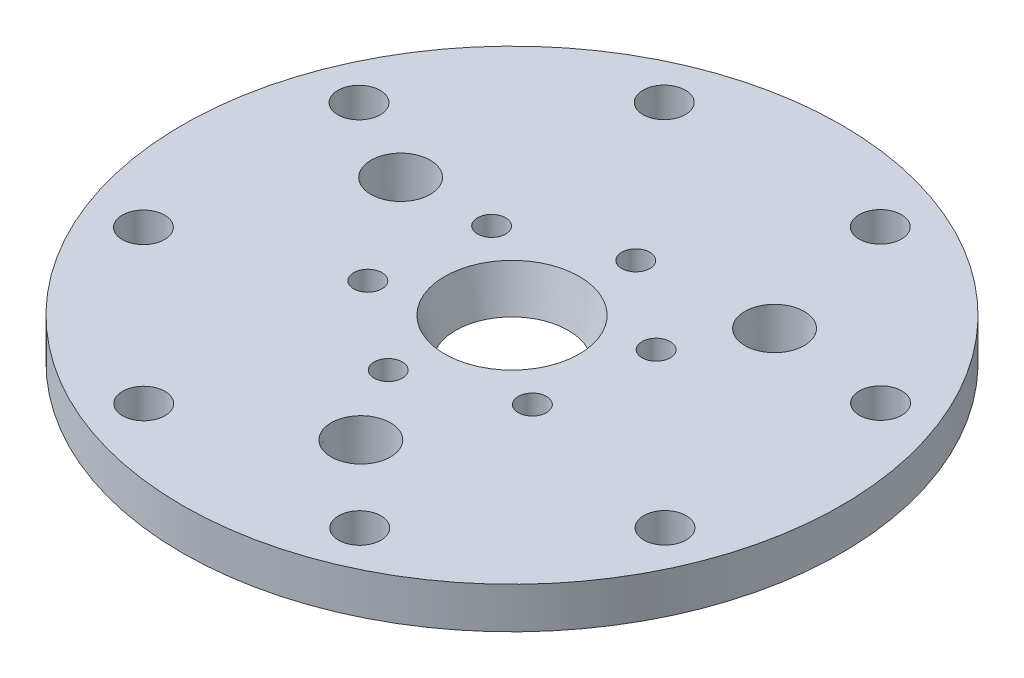
SolidWorks part; units mm, degrees
material "AISI 1020"
ref_plane "Front Plane" through (0, 0, 0) normal (0, 0, 1) x (1, 0, 0)
ref_plane "Top Plane" through (0, 0, 0) normal (0, 1, 0) x (1, 0, 0)
ref_plane "Right Plane" through (0, 0, 0) normal (1, 0, 0) x (0, 0, -1)
sketch "Sketch1" plane through (0, 0, 0) normal (0, 1, 0) x (1, 0, 0)
  circle A0 centre (0, 0) radius 76.2
  dimension "D1" = 152.4
extrude "Boss-Extrude1" add sketch "Sketch1" along normal blind 9.525 contours A0
sketch "Sketch5" plane through (0, 0, 0) normal (0, 0, 1) x (1, 0, 0)
  line L0 (0, 0) -> (0, 29.9809) construction
  line L1 (0, 0) -> (0, 9.525)
  line L2 (13, 0) -> (15.5522, 9.525)
  line L4 (76.2, 9.525) -> (-76.2, 9.525) construction
  line L6 (-76.2, 0) -> (76.2, 0) construction
  line L7 (0, 0) -> (13, 0)
  line L8 (15.5522, 9.525) -> (0, 9.525)
  line L9 (13, 0) -> (13, 9.525) construction
  dimension "D1" = 13
  dimension "D3" = 15
revolve "Cut-Revolve1" cut sketch "Sketch5" angle 360 about L0
sketch "Sketch6" plane through (0, 0, 0) normal (0, 1, 0) x (1, 0, 0)
  line L0 (0, 0) -> (46.194, 19.1342) construction
  line L1 (0, 0) -> (76.2, 0) construction
  circle A0 centre (46.194, 19.1342) radius 2.75
  circle A1 centre (0, 0) radius 76.2 construction
  dimension "D1" = 5.5
  dimension "D2" = 50
  dimension "D3" = 22.5
extrude "Cut-Extrude3" [suppressed] cut sketch "Sketch6" along normal through all
pattern_circular "CirPattern1" [suppressed] count 8 over 360
sketch "Sketch7" plane through (0, 9.525, 0) normal (0, 1, 0) x (1, 0, 0)
  line L0 (0, 0) -> (33.0117, 27.7001) construction
  line L1 (0, 0) -> (54.5383, 0) construction
  circle A0 centre (33.0117, 27.7001) radius 6.35
  circle A1 centre (0, 0) radius 55 construction
  circle A2 centre (33.0117, 27.7001) radius 11.9062 construction
  circle A3 centre (0, 0) radius 31.1875 construction
  dimension "D1" = 12.7
  dimension "D4" = 110
  dimension "D5" = 23.8125
  dimension "D3" = 40
sketch "Sketch8" plane through (0, 9.525, 0) normal (0, 1, 0) x (1, 0, 0)
  line L0 (0, 0) -> (17.5, 0) construction
  dimension "D1" = 17.5
sketch "Sketch9" plane through (0, 9.525, 0) normal (0, 1, 0) x (1, 0, 0)
  circle A0 centre (0, 0) radius 65.2 construction
  dimension "D1" = 130.4
hole_wizard "3/8 (0.375) Diameter Hole1" [suppressed] positions "Sketch10" profile "Sketch11" hole size "3/8" standard "ANSI Inch"
sketch "Sketch10" plane through (0, 10, 0) normal (0, 1, 0) x (1, 0, 0)
  circle A0 centre (0, 0) radius 65.2 construction
  point P0 (-65.2, 0)
sketch "Sketch11" plane through (-65.2, 10, 0) normal (1, 0, 0) x (0, 0, 1)
  line L0 (0, 0) -> (0, 10)
  line L1 (0, 10) -> (4.7625, 10)
  line L2 (4.7625, 10) -> (4.7625, 0)
  line L5 (4.7625, 0) -> (0, 0)
  line L11 (0, -6.35) -> (0, 107.95) construction
  dimension "Thru Hole Dia." = 9.525
  dimension "Thru Hole Depth" = 10
pattern_circular "CirPattern4" [suppressed] count 8 over 360
hole_wizard "Tap Drill for M4x0.7 Tap1" [suppressed] positions "Sketch12" profile "Sketch13" hole size "M4x0.7" standard "ANSI Metric"
sketch "Sketch12" plane through (0, 10, 0) normal (0, 1, 0) x (1, 0, 0)
  point P0 (17.5, 0)
sketch "Sketch13" plane through (17.5, 10, 0) normal (1, 0, 0) x (0, 0, 1)
  line L0 (0, 0) -> (0, 8.9914)
  line L1 (0, 8.9914) -> (1.65, 8)
  line L2 (1.65, 8) -> (1.65, 0)
  line L5 (1.65, 0) -> (0, 0)
  line L10 (0, 8.9914) -> (-1.65, 8) construction
  line L11 (0, -6.35) -> (0, 107.95) construction
  dimension "Hole Dia." = 3.3
  dimension "Hole Depth" = 8
  dimension "Drill Angle" = 118
cosmetic thread "Cosmetic Thread5" [suppressed] parameters "D2"=4.1656
pattern_circular "CirPattern5" [suppressed] count 6 over 360
cosmetic thread "Cosmetic Thread6" [suppressed] parameters "D2"=4.1656
cosmetic thread "Cosmetic Thread7" [suppressed] parameters "D2"=4.1656
cosmetic thread "Cosmetic Thread8" [suppressed] parameters "D2"=4.1656
cosmetic thread "Cosmetic Thread9" [suppressed] parameters "D2"=4.1656
cosmetic thread "Cosmetic Thread10" [suppressed] parameters "D2"=4.1656
hole_wizard "1/4 NPT Tapped Hole1" positions "Sketch14" profile "Sketch15" size "1/4" standard "ANSI Inch" end condition through all
sketch "Sketch14" plane through (0, 9.525, 0) normal (0, 1, 0) x (1, 0, 0)
  point P0 (33.0117, 27.7001)
sketch "Sketch15" plane through (33.0117, 9.525, -27.7001) normal (1, 0, 0) x (0, 0, 1)
  line L0 (0, 0) -> (0, 9.525)
  line L1 (0, 9.525) -> (5.5626, 9.525)
  line L2 (-6.558, 10.0203) -> (-6.858, 0) construction
  line L3 (5.5626, 9.525) -> (5.5626, 10.0203)
  line L4 (5.5626, 10.0203) -> (6.558, 10.0203)
  line L5 (6.558, 10.0203) -> (6.858, 0)
  line L7 (6.858, 0) -> (0, 0)
  line L8 (0, -6.35) -> (0, 107.95) construction
  line L11 (-5.5626, 10.0203) -> (-6.558, 10.0203) construction
  dimension "Thru Tap Drill Dia." = 11.1252
  dimension "Thru Tap Drill Depth" = 9.525
  dimension "Thread Dia." = 13.716
  dimension "Thread Angle" = 3.43
  dimension "Thread Depth" = 10.0203
pattern_circular "CirPattern6" count 3 over 360 about axis through (0, 0, 0) along (0, 1, 0) of "1/4 NPT Tapped Hole1"
hole_wizard "3/8 Clearance Hole1" positions "Sketch16" profile "Sketch17" hole size "3/8" standard "ANSI Inch" end condition through all
sketch "Sketch16" plane through (0, 9.525, 0) normal (0, 1, 0) x (1, 0, 0)
  line L0 (60.208, 25.0136) -> (60.2072, 25.0136) construction
  line L1 (60.2581, -24.8888) -> (60.2574, -24.8885) construction
  line L2 (24.8862, 60.2645) -> (24.8856, 60.2643) construction
  line L3 (-25.0162, 60.2143) -> (-25.0165, 60.2141) construction
  line L4 (-60.2169, -25.0099) -> (-60.2169, -25.0096) construction
  line L5 (-24.8951, -60.2608) -> (-24.8954, -60.2602) construction
  point P0 (60.2072, 25.0136)
  point P4 (60.2574, -24.8885)
  point P8 (24.8856, 60.2643)
  point P12 (-25.0165, 60.2141)
  point P16 (-60.2671, 24.8925)
  point P19 (-60.2169, -25.0096)
  point P23 (-24.8954, -60.2602)
  point P27 (25.0067, -60.2101)
sketch "Sketch17" plane through (60.2072, 9.525, -25.0136) normal (1, 0, 0) x (0, 0, 1)
  line L0 (0, 0) -> (0, 9.525)
  line L1 (0, 9.525) -> (4.9022, 9.525)
  line L2 (4.9022, 9.525) -> (4.9022, 0)
  line L5 (4.9022, 0) -> (0, 0)
  line L11 (0, -6.35) -> (0, 107.95) construction
  dimension "Thru Hole Dia." = 9.8044
  dimension "Thru Hole Depth" = 9.525
hole_wizard "1/4 Clearance Hole1" positions "Sketch18" profile "Sketch19" hole size "1/4" standard "ANSI Inch" end condition through all
sketch "Sketch18" plane through (0, 9.525, 0) normal (0, 1, 0) x (1, 0, 0)
  point P0 (3.33, 25.2942)
  point P3 (-20.2404, 15.531)
  point P8 (20.2404, -15.531)
  point P13 (-23.5705, -9.7632)
  point P19 (-3.33, -25.2942)
  point P22 (23.5705, 9.7632)
sketch "Sketch19" plane through (3.33, 9.525, -25.2942) normal (1, 0, 0) x (0, 0, 1)
  line L0 (0, 0) -> (0, 9.525)
  line L1 (0, 9.525) -> (3.2639, 9.525)
  line L2 (3.2639, 9.525) -> (3.2639, 0)
  line L5 (3.2639, 0) -> (0, 0)
  line L11 (0, -6.35) -> (0, 107.95) construction
  dimension "Thru Hole Dia." = 6.5278
  dimension "Thru Hole Depth" = 9.525
